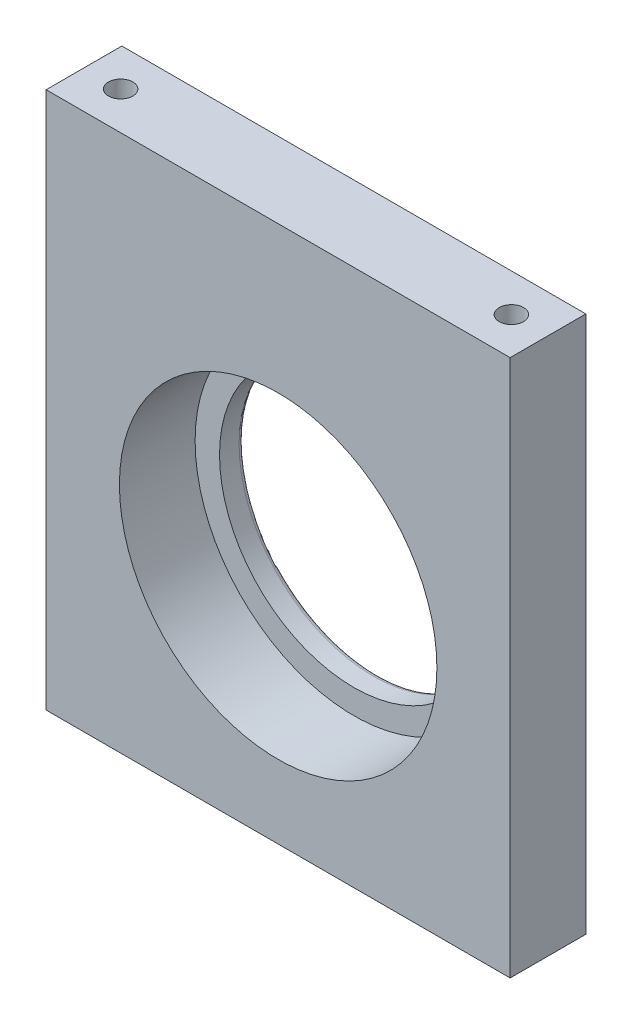
SolidWorks part; units mm, degrees
ref_plane "Plan de face" through (0, 0, 0) normal (0, 0, 1) x (1, 0, 0)
ref_plane "Plan de dessus" through (0, 0, 0) normal (0, 1, 0) x (1, 0, 0)
ref_plane "Plan de droite" through (0, 0, 0) normal (1, 0, 0) x (0, 0, -1)
sketch "Esquisse1" plane through (0, 0, 0) normal (0, 0, 1) x (1, 0, 0)
  line L0 (-95, 0) -> (95, 0)
  line L1 (95, 0) -> (95, 220)
  line L2 (95, 220) -> (-95, 220)
  line L3 (-95, 220) -> (-95, 0)
  line L4 (0, -1000) -> (0, 49000) construction
  circle A1 centre (0, 95) radius 65
  point P4 (0, 0)
  dimension "D3" = 95
  dimension "D5" = 130
  dimension "D1" = 220
  dimension "D2" = 190
  dimension "D4" = 95
extrude "Boss.-Extru.1" add sketch "Esquisse1" along normal blind 31
sketch "Esquisse2" plane through (0, 220, 0) normal (0, 1, 0) x (1, 0, 0)
  line L0 (-95, -31) -> (-95, 0) construction
  line L1 (95, -31) -> (-95, -31) construction
  circle A0 centre (-80, -15.5) radius 5
  dimension "D1" = 10
  dimension "D2" = 15
  dimension "D3" = 15.5
extrude "Enlèv. mat.-Extru.1" cut sketch "Esquisse2" against normal blind 15
mirror "Symétrie1" about plane through (0, 0, 0) normal (1, 0, 0) of "Enlèv. mat.-Extru.1"
sketch "Esquisse4" plane through (0, 0, 0) normal (0, 0, 1) x (1, 0, 0)
  line L1 (-75, 20) -> (75, 20)
  line L2 (-75, 20) -> (-75, 170)
  line L3 (-75, 170) -> (75, 170)
  line L4 (75, 20) -> (75, 170)
  line L5 (-75, 20) -> (75, 170) construction
  line L6 (-75, 170) -> (75, 20) construction
  circle A0 centre (0, 95) radius 55
  dimension "D1" = 110
  dimension "D2" = 150
  dimension "D3" = 150
extrude "Boss.-Extru.2" add sketch "Esquisse4" against normal blind 10
fillet "Congé1" radius 2 5 edges at (55, 95, -10) (75, 95, 0) (0, 20, 0) (-75, 95, 0) (0, 170, 0)
equation "\"D3@Esquisse2\"=31/2"
